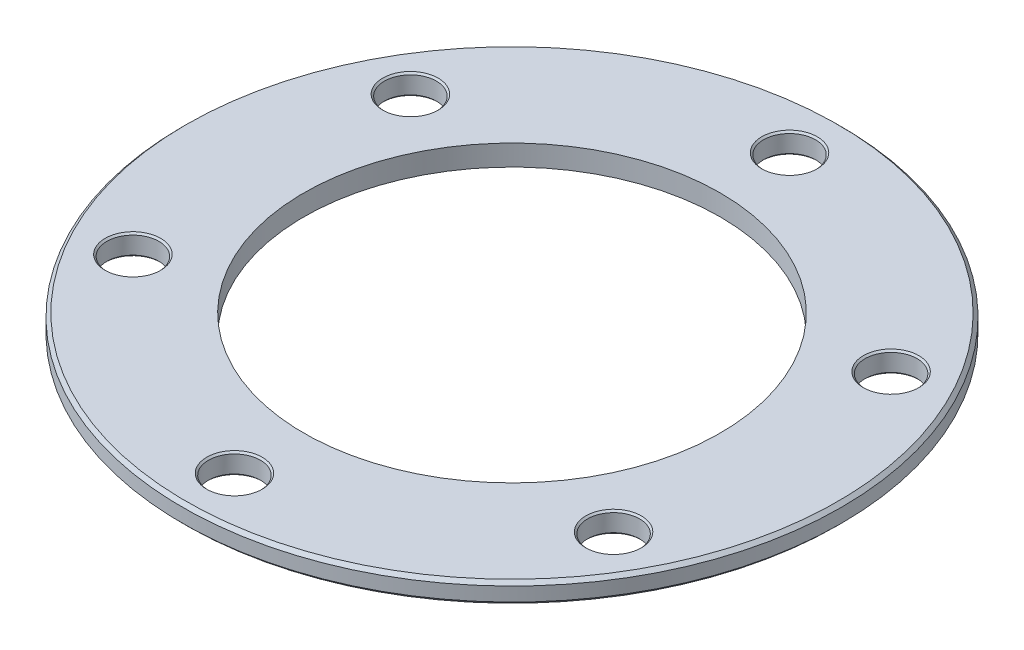
SolidWorks part; units mm, degrees
material "ABS Plastic, közepes szilárdásgú"
ref_plane "Front Plane" through (0, 0, 0) normal (0, 0, 1) x (1, 0, 0)
ref_plane "Top Plane" through (0, 0, 0) normal (0, 1, 0) x (1, 0, 0)
ref_plane "Right Plane" through (0, 0, 0) normal (1, 0, 0) x (0, 0, -1)
sketch "Sketch1" plane through (0, 0, 0) normal (0, 0, 1) x (1, 0, 0)
  line L0 (95, 5) -> (0, 5)
  line L1 (0, 5) -> (0, -1)
  line L2 (0, -1) -> (95, -1)
  line L3 (95, -1) -> (95, 5)
  line L4 (0, 5) -> (0, -1) construction
  dimension "D1" = 6
  dimension "D2" = 95
revolve "Revolve1" add sketch "Sketch1" angle 360 about L4
hole_wizard "Hole1" positions "Sketch3" profile "Sketch2" legacy
sketch "Sketch3" plane through (0, -1, 0) normal (0, -1, 0) x (-1, 0, 0)
  point P0 (0, 0)
sketch "Sketch2" plane through (0, -1, 0) normal (1, 0, 0) x (0, 0, -1)
  line L0 (0, 0) -> (0, 6)
  line L1 (0, 6) -> (60, 6)
  line L2 (60, 6) -> (60, 0)
  line L3 (60, 0) -> (0, 0)
  line L4 (0, 110) -> (0, -10) construction
  dimension "Diameter" = 120
  dimension "Depth" = 6
hole_wizard "9/16 Clearance Hole1" positions "Sketch5" profile "Sketch4" hole size "9/16" standard "ANSI Inch"
sketch "Sketch5" plane through (0, -1, 0) normal (0, -1, 0) x (-1, 0, 0)
  point P0 (69.282, 40)
  point P1 (0, 80)
sketch "Sketch4" plane through (-69.282, -1, -40) normal (1, 0, 0) x (0, 0, -1)
  line L0 (0, 0) -> (0, 6)
  line L1 (0, 6) -> (7.5, 6)
  line L2 (7.5, 6) -> (7.5, 0)
  line L5 (7.5, 0) -> (0, 0)
  line L11 (0, -6.35) -> (0, 107.95) construction
  dimension "Thru Hole Dia." = 15
  dimension "Thru Hole Depth" = 6
hole_wizard "9/16 Clearance Hole2" positions "Sketch7" profile "Sketch6" hole size "9/16" standard "ANSI Inch"
sketch "Sketch7" plane through (0, 5, 0) normal (0, 1, 0) x (1, 0, 0)
  point P0 (-69.282, -40)
  point P1 (69.282, 40)
  point P2 (69.282, -40)
  point P3 (0, -80)
sketch "Sketch6" plane through (-69.282, 5, 40) normal (1, 0, 0) x (0, 0, 1)
  line L0 (0, 0) -> (0, 6)
  line L1 (0, 6) -> (7.5, 6)
  line L2 (7.5, 6) -> (7.5, 0)
  line L5 (7.5, 0) -> (0, 0)
  line L11 (0, -6.35) -> (0, 107.95) construction
  dimension "Thru Hole Dia." = 15
  dimension "Thru Hole Depth" = 6
chamfer "Chamfer1" distance 0.5 angle 45 12 edges at (69.282, -1, -32.5) (0, -1, 87.5) (69.282, -1, 47.5) (-69.282, -1, 47.5) (-69.282, 5, -47.5) (69.282, 5, 47.5) (-69.282, -1, -47.5) (0, 5, 87.5) (0, 5, -87.5) (0, -1, -87.5) (-69.282, 5, 47.5) (69.282, 5, -32.5)
chamfer "Chamfer2" distance 1 angle 45 2 edges at (95, -1, 0) (95, 5, 0)
